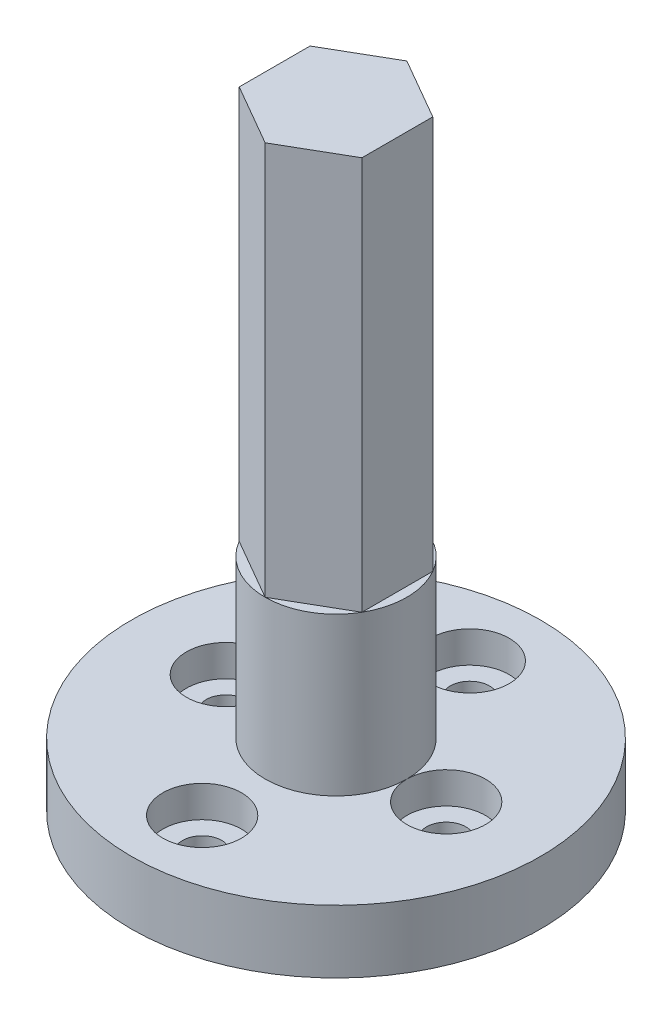
SolidWorks part; units mm, degrees
ref_plane "Alzado" through (0, 0, 0) normal (0, 0, 1) x (1, 0, 0)
ref_plane "Planta" through (0, 0, 0) normal (0, 1, 0) x (1, 0, 0)
ref_plane "Vista lateral" through (0, 0, 0) normal (1, 0, 0) x (0, 0, -1)
sketch "Croquis3" plane through (0, 0, 0) normal (0, 1, 0) x (1, 0, 0)
  circle A0 centre (0, 0) radius 13
  dimension "D1" = 26
extrude "Saliente-Extruir1" add sketch "Croquis3" along normal blind 4
sketch "Croquis4" plane through (0, 4, 0) normal (0, 1, 0) x (1, 0, 0)
  circle A0 centre (0, 0) radius 4.5
  dimension "D1" = 9
extrude "Saliente-Extruir2" add sketch "Croquis4" along normal blind 35
sketch "Croquis7" plane through (0, 0, 0) normal (0, -1, 0) x (1, 0, 0)
  circle A0 centre (0, 0) radius 12
  dimension "D1" = 24
sketch "Croquis8" plane through (0, 0, 0) normal (0, -1, 0) x (1, 0, 0)
  line L0 (0, -10.2812) -> (0, 10.4112) construction
  line L1 (-11.52, 0) -> (11.5297, 0) construction
  circle A1 centre (0, 8.5) radius 1.25
  circle A2 centre (0, -8.5) radius 1.25
  circle A3 centre (-7, 0) radius 1.25
  circle A4 centre (7, 0) radius 1.25
  dimension "D1" = 8.5
  dimension "D2" = 2.5
  dimension "D3" = 7
extrude "Cortar-Extruir3" cut sketch "Croquis8" against normal through all both and the other way through all
sketch "Croquis10" plane through (0, 4, 0) normal (0, 1, 0) x (1, 0, 0)
  circle A0 centre (0, -8.5) radius 1.25 construction
  circle A1 centre (0, 8.5) radius 1.25 construction
  circle A2 centre (0, -8.5) radius 1.25 construction
  circle A3 centre (0, 8.5) radius 1.25 construction
  circle A4 centre (0, 8.5) radius 2.5
  circle A5 centre (0, -8.5) radius 2.5
  circle A6 centre (7, 0) radius 1.25 construction
  circle A7 centre (-7, 0) radius 1.25 construction
  circle A8 centre (7, 0) radius 1.25
  circle A9 centre (-7, 0) radius 1.25
  circle A10 centre (-7, 0) radius 2.5
  circle A11 centre (7, 0) radius 2.5
  dimension "D1" = 5
  dimension "D2" = 5
extrude "Cortar-Extruir5" cut sketch "Croquis10" against normal blind 2 and the other way through all
sketch "Croquis9" plane through (0, 0, 0) normal (0, 1, 0) x (1, 0, 0)
  circle A0 centre (0, 0) radius 1.625
  dimension "D1" = 3.25
extrude "Cortar-Extruir4" cut sketch "Croquis9" along normal blind 3
sketch "Croquis11" plane through (0, 0, 0) normal (0, -1, 0) x (1, 0, 0)
  circle A0 centre (0, 0) radius 4
  dimension "D1" = 8
extrude "Cortar-Extruir6" cut sketch "Croquis11" against normal blind 0.5
sketch "Croquis12" plane through (0, 39, 0) normal (0, 1, 0) x (1, 0, 0)
  line L1 (0, 4.5) -> (-3.8971, 2.25)
  line L2 (-3.8971, 2.25) -> (-3.8971, -2.25)
  line L3 (-3.8971, -2.25) -> (0, -4.5)
  line L4 (0, -4.5) -> (3.8971, -2.25)
  line L5 (3.8971, -2.25) -> (3.8971, 2.25)
  line L6 (3.8971, 2.25) -> (0, 4.5)
  circle A0 centre (0, 0) radius 4.5 construction
  circle A1 centre (0, 0) radius 4.5 construction
  circle A2 centre (0, 0) radius 4.5 construction
extrude "Cortar-Extruir7" cut sketch "Croquis12" against normal blind 25 flip side to cut
